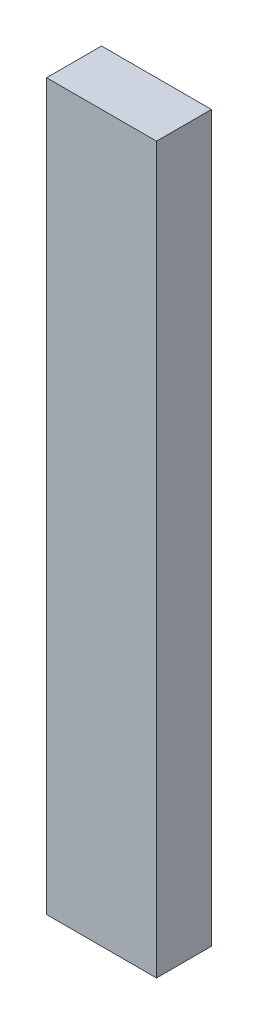
SolidWorks part; units mm, degrees
ref_plane "Front Plane" through (0, 0, 0) normal (0, 0, 1) x (1, 0, 0)
ref_plane "Top Plane" through (0, 0, 0) normal (0, 1, 0) x (1, 0, 0)
ref_plane "Right Plane" through (0, 0, 0) normal (1, 0, 0) x (0, 0, -1)
sketch "Sketch1" plane through (0, 0, 0) normal (0, 1, 0) x (1, 0, 0)
  line L1 (-50.8, -25.4) -> (50.8, -25.4)
  line L2 (-50.8, -25.4) -> (-50.8, 25.4)
  line L3 (-50.8, 25.4) -> (50.8, 25.4)
  line L4 (50.8, -25.4) -> (50.8, 25.4)
  line L5 (-50.8, -25.4) -> (50.8, 25.4) construction
  line L6 (-50.8, 25.4) -> (50.8, -25.4) construction
  point P0 (0, 0)
  dimension "D1" = 101.6
  dimension "D2" = 50.8
extrude "Boss-Extrude1" add sketch "Sketch1" along normal blind 670
